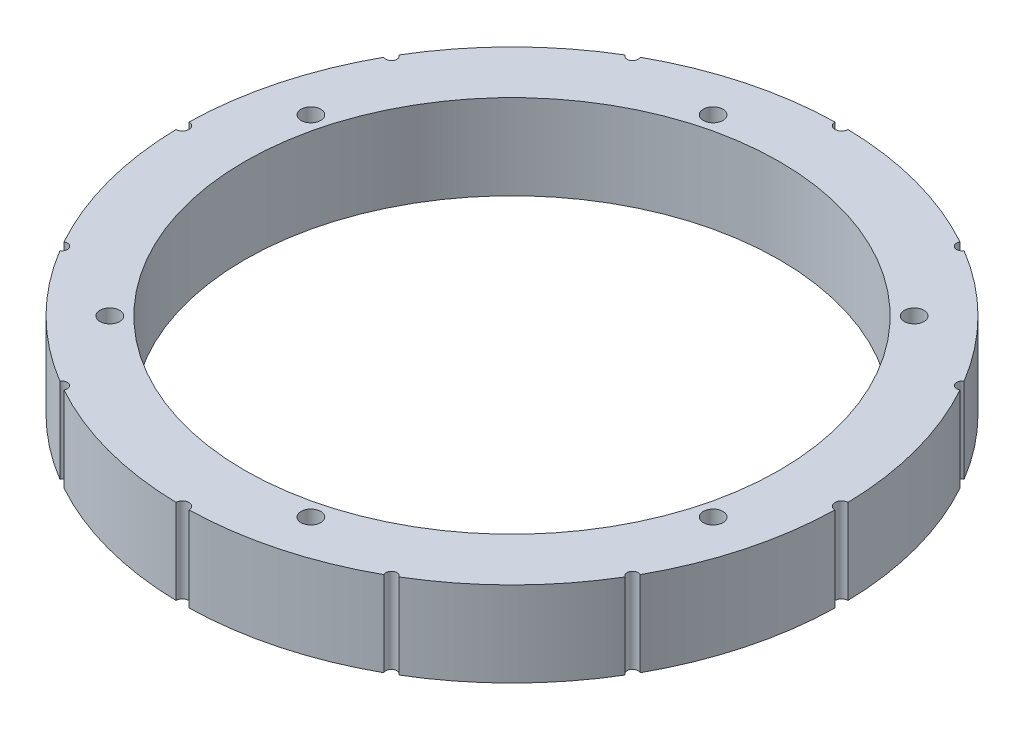
SolidWorks part; units mm, degrees
ref_plane "前视基准面" through (0, 0, 0) normal (0, 0, 1) x (1, 0, 0)
ref_plane "上视基准面" through (0, 0, 0) normal (0, 1, 0) x (1, 0, 0)
ref_plane "右视基准面" through (0, 0, 0) normal (1, 0, 0) x (0, 0, -1)
sketch "草图1" plane through (0, 0, 0) normal (0, 1, 0) x (1, 0, 0)
  circle A0 centre (0, 0) radius 40.9
  circle A1 centre (0, 0) radius 50.4
  dimension "D1" = 81.8
  dimension "D2" = 100.8
extrude "凸台-拉伸1" add sketch "草图1" against normal blind 13 contours A0
sketch "草图2" plane through (0, -13, 0) normal (0, -1, 0) x (1, 0, 0)
  line L0 (0, -75.2808) -> (0, 56.4382) construction
  circle A0 centre (0, 50.4) radius 1
  circle A1 centre (0, 0) radius 50.4 construction
  circle A2 centre (50.4, 0) radius 1
  circle A3 centre (0, -50.4) radius 1
  circle A4 centre (-50.4, 0) radius 1
  circle A5 centre (-25.2, 43.6477) radius 0.85
  circle A6 centre (25.2, 43.6477) radius 0.85
  circle A7 centre (43.6477, 25.2) radius 0.85
  circle A8 centre (43.6477, -25.2) radius 0.85
  circle A9 centre (25.2, -43.6477) radius 0.85
  circle A10 centre (-25.2, -43.6477) radius 0.85
  circle A11 centre (-43.6477, -25.2) radius 0.85
  circle A12 centre (-43.6477, 25.2) radius 0.85
  point P14 (0, 0)
  point P33 (0, 0)
  dimension "D1" = 2
  dimension "D3" = 1.7
  dimension "D4" = 30
  dimension "D2" = 4
  dimension "D5" = 4
extrude "切除-拉伸1" cut sketch "草图2" against normal blind 13
sketch "草图3" plane through (0, 0, 0) normal (0, 1, 0) x (1, 0, 0)
  line L0 (0, -59.1889) -> (0, 55.0049) construction
  line L1 (-11.2586, 42.0178) -> (0, 0) construction
  circle A0 centre (-11.2586, 42.0178) radius 1.5
  circle A2 centre (0, 0) radius 40.9 construction
  point P21 (0, 0)
  dimension "D1" = 3
  dimension "D2" = 43.5
  dimension "D3" = 15
extrude "切除-拉伸2" cut sketch "草图3" against normal blind 5
cosmetic thread "装饰螺纹线1" parameters "D2"=4
sketch "草图4" plane through (0, 0, 0) normal (1, 0, 0) x (0, 0, -1)
  line L0 (0, 10.2914) -> (0, -21.6359) construction
pattern_circular "阵列(圆周)1" count 6 every 60 about axis through (0, 0, 0) along (0, 1, 0) of "切除-拉伸2"
